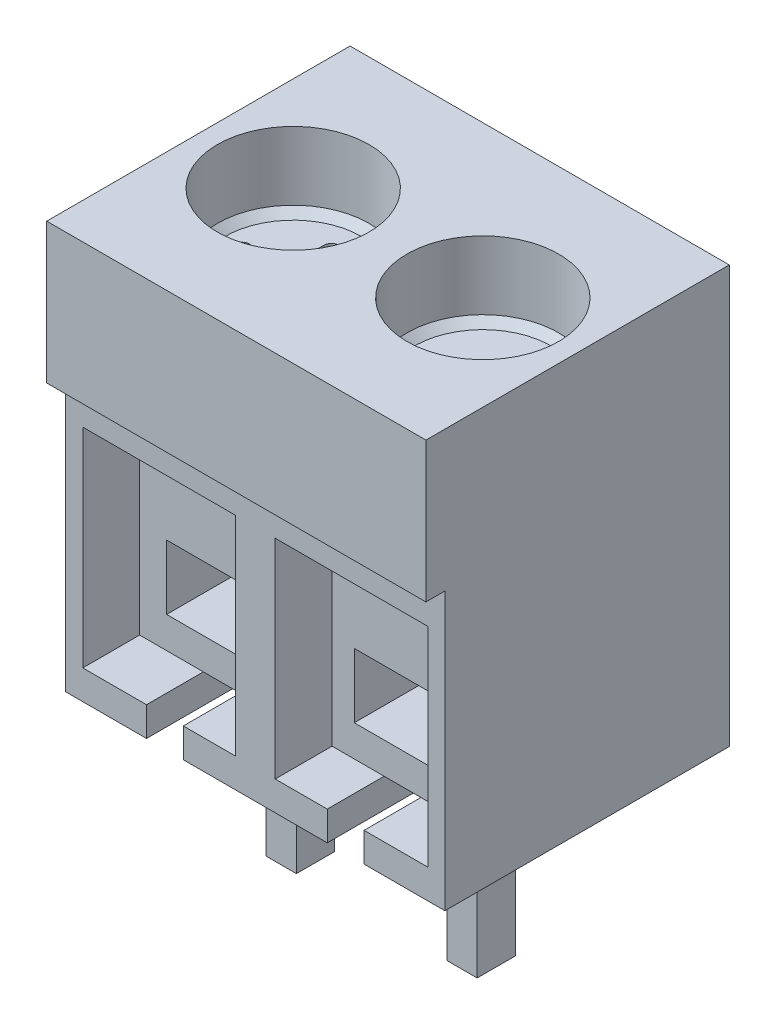
SolidWorks part; units mm, degrees
ref_plane "Front Plane" through (0, 0, 0) normal (0, 0, 1) x (1, 0, 0)
ref_plane "Top Plane" through (0, 0, 0) normal (0, 1, 0) x (1, 0, 0)
ref_plane "Right Plane" through (0, 0, 0) normal (1, 0, 0) x (0, 0, -1)
sketch "Croquis1" plane through (0, 0, 0) normal (0, 0, 1) x (1, 0, 0)
  line L1 (-5, 5.5) -> (5, 5.5)
  line L2 (-5, 5.5) -> (-5, -5.5)
  line L3 (-5, -5.5) -> (5, -5.5)
  line L4 (5, 5.5) -> (5, -5.5)
  line L5 (-5, 5.5) -> (5, -5.5) construction
  line L6 (-5, -5.5) -> (5, 5.5) construction
  point P0 (0, 0)
extrude "Saliente-Extruir1" add sketch "Croquis1" along normal blind 8
sketch "Croquis2" plane through (0, 5.5, 0) normal (0, 1, 0) x (1, 0, 0)
  line L0 (0, 0) -> (0, -4) construction
  line L1 (0, -4) -> (2.5, -4) construction
  circle A0 centre (2.5, -4) radius 2
  circle A1 centre (-2.5, -4) radius 2
extrude "Cortar-Extruir1" cut sketch "Croquis2" against normal blind 2
sketch "Croquis3" plane through (0, 0, 8) normal (0, 0, 1) x (1, 0, 0)
  line L0 (-5, -5.5) -> (-5, 1.803)
  line L1 (-5, 5.5) -> (-5, -5.5) construction
  line L2 (-5, 1.803) -> (5, 1.803)
  line L3 (5, -5.5) -> (5, 5.5) construction
  line L4 (5, 1.803) -> (5, -5.5)
  line L5 (5, -5.5) -> (-5, -5.5)
extrude "Cortar-Extruir2" cut sketch "Croquis3" against normal blind 0.5
sketch "Croquis4" plane through (0, 0, 7.5) normal (0, 0, 1) x (1, 0, 0)
  line L0 (0, 0) -> (0, -1.9785) construction
  line L1 (-4.5495, 0.7713) -> (-0.5254, 0.7713)
  line L2 (-4.5495, 0.7713) -> (-4.5495, -4.7283)
  line L3 (-4.5495, -4.7283) -> (-0.5254, -4.7283)
  line L4 (-0.5254, 0.7713) -> (-0.5254, -4.7283)
  line L5 (-4.5495, 0.7713) -> (-0.5254, -4.7283) construction
  line L6 (-4.5495, -4.7283) -> (-0.5254, 0.7713) construction
  line L7 (0.5254, 0.7713) -> (0.5254, -4.7283)
  line L8 (4.5495, -4.7283) -> (0.5254, -4.7283)
  line L9 (4.5495, 0.7713) -> (4.5495, -4.7283)
  line L10 (4.5495, 0.7713) -> (0.5254, 0.7713)
  point P0 (-2.5374, -1.9785)
extrude "Cortar-Extruir3" cut sketch "Croquis4" against normal blind 1.5
sketch "Croquis5" plane through (0, 0, 6) normal (0, 0, 1) x (1, 0, 0)
  line L0 (0, 0) -> (0, -2.448) construction
  line L1 (-3.8382, -2.2021) -> (-1.1107, -2.2021)
  line L2 (-3.8382, -2.2021) -> (-3.8382, -3.9011)
  line L3 (-3.8382, -3.9011) -> (-1.1107, -3.9011)
  line L4 (-1.1107, -2.2021) -> (-1.1107, -3.9011)
  line L7 (1.1107, -2.2021) -> (1.1107, -3.9011)
  line L8 (3.8382, -3.9011) -> (1.1107, -3.9011)
  line L9 (3.8382, -2.2021) -> (3.8382, -3.9011)
  line L10 (3.8382, -2.2021) -> (1.1107, -2.2021)
  point P0 (-2.2244, -3.0516)
extrude "Cortar-Extruir4" cut sketch "Croquis5" against normal blind 3.5
sketch "Croquis6" plane through (0, 3.5, 0) normal (0, 1, 0) x (1, 0, 0)
  line L0 (0, 0) -> (0, -3.3878) construction
  line L1 (-2.796, -4.2158) -> (-2.796, -5.1702)
  line L2 (-2.3899, -2.8959) -> (-2.3899, -3.8503)
  line L3 (-2.796, -2.8959) -> (-2.796, -3.8503)
  line L4 (2.3899, -4.2158) -> (2.3899, -5.1702)
  line L5 (-3.8113, -3.8503) -> (-2.796, -3.8503)
  line L6 (-3.8113, -4.2158) -> (-2.796, -4.2158)
  line L7 (-2.3899, -3.8503) -> (-1.3746, -3.8503)
  line L8 (-2.3899, -4.2158) -> (-1.3746, -4.2158)
  line L9 (-2.3899, -4.2158) -> (-2.3899, -5.1702)
  line L10 (2.3899, -4.2158) -> (1.3746, -4.2158)
  line L11 (2.3899, -3.8503) -> (1.3746, -3.8503)
  line L12 (3.8113, -4.2158) -> (2.796, -4.2158)
  line L13 (3.8113, -3.8503) -> (2.796, -3.8503)
  line L14 (2.796, -2.8959) -> (2.796, -3.8503)
  line L15 (2.3899, -2.8959) -> (2.3899, -3.8503)
  line L16 (2.796, -4.2158) -> (2.796, -5.1702)
  arc A0 (-2.3899, -2.8959) -> (-2.796, -2.8959) centre (-2.593, -2.8959) ccw
  arc A1 (-2.796, -5.1702) -> (-2.3899, -5.1702) centre (-2.593, -5.1702) ccw
  arc A2 (-3.8113, -3.8503) -> (-3.8113, -4.2158) centre (-3.8113, -4.033) ccw
  arc A3 (-1.3746, -4.2158) -> (-1.3746, -3.8503) centre (-1.3746, -4.033) ccw
  arc A4 (1.3746, -4.2158) -> (1.3746, -3.8503) centre (1.3746, -4.033) cw
  arc A5 (3.8113, -3.8503) -> (3.8113, -4.2158) centre (3.8113, -4.033) cw
  arc A6 (2.796, -5.1702) -> (2.3899, -5.1702) centre (2.593, -5.1702) cw
  arc A7 (2.3899, -2.8959) -> (2.796, -2.8959) centre (2.593, -2.8959) cw
  point P5 (-2.593, -4.033)
  point P11 (-2.593, -4.033)
  point P37 (2.593, -4.033)
extrude "Cortar-Extruir5" cut sketch "Croquis6" against normal blind 1 draft 3
chamfer "Chaflán1" distance 0.2 angle 45 2 edges at (2.5, 3.5, 6) (-2.5, 3.5, 2)
sketch "Croquis7" plane through (0, 0, 7.5) normal (0, 0, 1) x (1, 0, 0)
  line L0 (0, -5.5) -> (0, -3.0472) construction
  line L1 (-5, -5.5) -> (5, -5.5) construction
  line L2 (-2.8691, -5.0793) -> (-2.8691, -5.6299)
  line L3 (-1.8981, -5.0793) -> (-1.8981, -4.7283)
  line L4 (-2.8691, -5.6299) -> (-1.8981, -5.6299)
  line L5 (-1.8981, -5.6299) -> (-1.8981, -5.0793)
  line L6 (2.8691, -4.7283) -> (2.8691, -5.0793)
  line L7 (1.8981, -4.7283) -> (2.8691, -4.7283)
  line L8 (1.8981, -5.6299) -> (1.8981, -5.0793)
  line L9 (2.8691, -5.6299) -> (1.8981, -5.6299)
  line L10 (-4.5495, -4.7283) -> (-0.5254, -4.7283) construction
  line L11 (-1.8981, -4.7283) -> (-2.8691, -4.7283)
  line L12 (-2.8691, -4.7283) -> (-2.8691, -5.0793)
  line L13 (1.8981, -5.0793) -> (1.8981, -4.7283)
  line L14 (2.8691, -5.0793) -> (2.8691, -5.6299)
extrude "Cortar-Extruir6" cut sketch "Croquis7" against normal through all
sketch "Croquis8" plane through (0, -4.7283, 0) normal (0, -1, 0) x (1, 0, 0)
  line L1 (-2.7831, 4.4316) -> (-1.9831, 4.4316)
  line L2 (-2.7831, 4.4316) -> (-2.7831, 3.4219)
  line L3 (-2.7831, 3.4219) -> (-1.9831, 3.4219)
  line L4 (-1.9831, 4.4316) -> (-1.9831, 3.4219)
  line L5 (-2.7831, 4.4316) -> (-1.9831, 3.4219) construction
  line L6 (-2.7831, 3.4219) -> (-1.9831, 4.4316) construction
  line L7 (0, 0) -> (0, 1.0605) construction
  line L8 (2.7831, 3.4219) -> (1.9831, 4.4316) construction
  line L9 (2.7831, 4.4316) -> (1.9831, 3.4219) construction
  line L10 (1.9831, 4.4316) -> (1.9831, 3.4219)
  line L11 (2.7831, 3.4219) -> (1.9831, 3.4219)
  line L12 (2.7831, 4.4316) -> (2.7831, 3.4219)
  line L13 (2.7831, 4.4316) -> (1.9831, 4.4316)
  point P0 (-2.3831, 3.9267)
  point P12 (2.3831, 3.9267)
extrude "Saliente-Extruir2" add sketch "Croquis8" along normal blind 5
chamfer "Chaflán2" distance 0.05 angle 45 8 edges at (-2.7831, -9.7283, 3.9267) (-2.3831, -9.7283, 4.4316) (-2.3831, -9.7283, 3.4219) (-1.9831, -9.7283, 3.9267) (2.3831, -9.7283, 4.4316) (1.9831, -9.7283, 3.9267) (2.3831, -9.7283, 3.4219) (2.7831, -9.7283, 3.9267)
